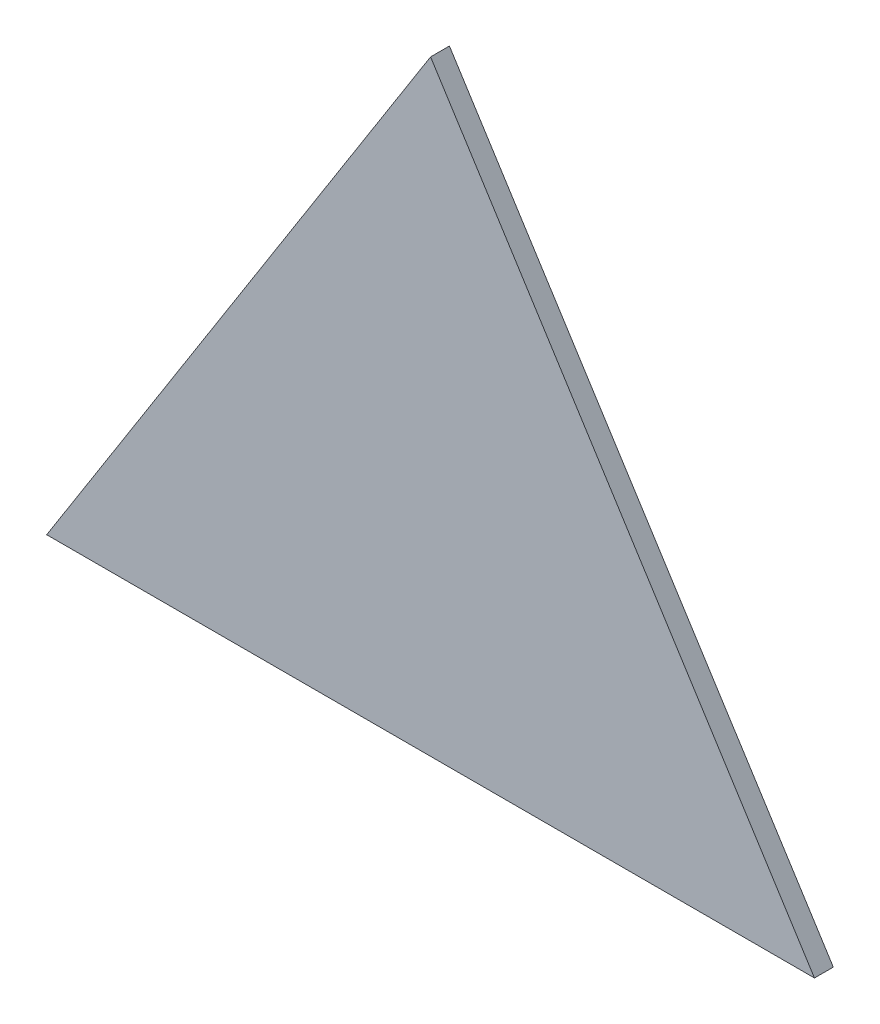
SolidWorks part; units mm, degrees
ref_plane "Front Plane" through (0, 0, 0) normal (0, 0, 1) x (1, 0, 0)
ref_plane "Top Plane" through (0, 0, 0) normal (0, 1, 0) x (1, 0, 0)
ref_plane "Right Plane" through (0, 0, 0) normal (1, 0, 0) x (0, 0, -1)
sketch "Sketch1" plane through (0, 0, 0) normal (0, 0, 1) x (1, 0, 0)
  line L0 (214.851, -133.9398) -> (204.6572, -117.854) construction
  line L1 (204.6572, -117.854) -> (194.4633, -133.9398) construction
  line L2 (194.4633, -133.9398) -> (214.851, -133.9398) construction
  line L3 (214.851, -133.9398) -> (204.6572, -117.854)
  line L4 (204.6572, -117.854) -> (194.4633, -133.9398)
  line L5 (194.4633, -133.9398) -> (214.851, -133.9398)
extrude "Boss-Extrude1" add sketch "Sketch1" along normal blind 0.5
